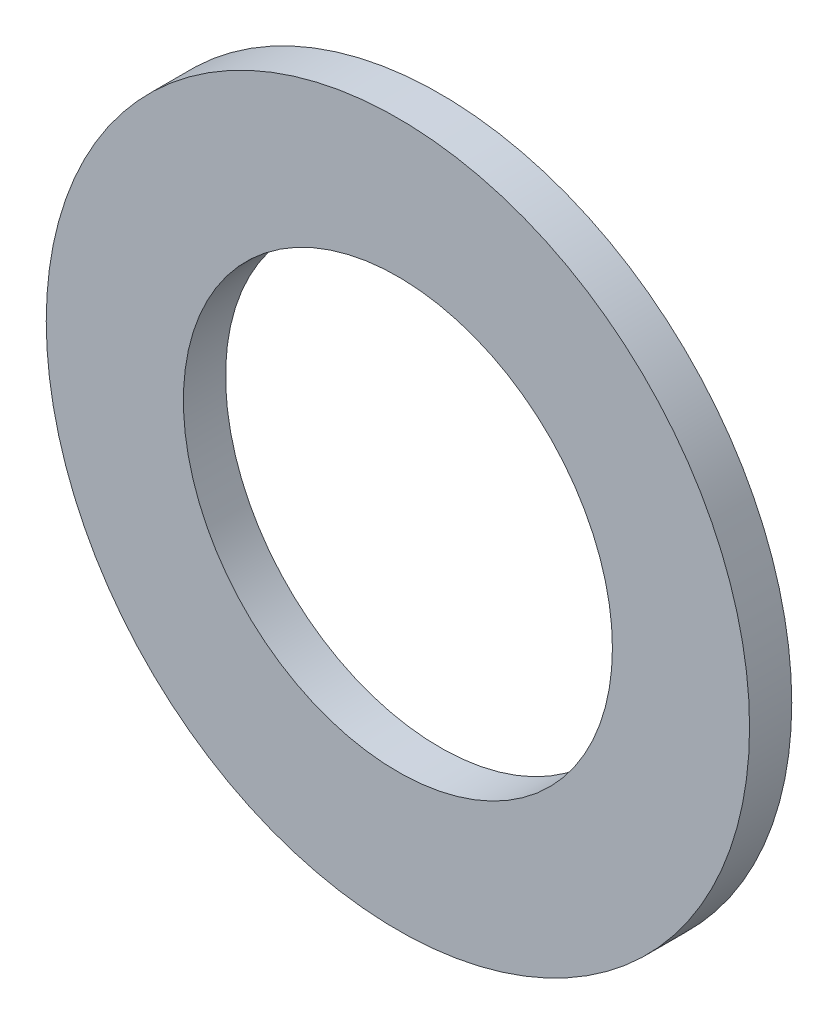
SolidWorks part; units mm, degrees
ref_plane "Front Plane" through (0, 0, 0) normal (0, 0, 1) x (1, 0, 0)
ref_plane "Top Plane" through (0, 0, 0) normal (0, 1, 0) x (1, 0, 0)
ref_plane "Right Plane" through (0, 0, 0) normal (1, 0, 0) x (0, 0, -1)
sketch "Sketch1" plane through (0, 0, 0) normal (1, 0, 0) x (0, 0, -1)
  line L0 (0, 0) -> (44.6003, 0) construction
  line L1 (0, 30.5) -> (0, 50)
  line L2 (0, 50) -> (6, 50)
  line L3 (6, 50) -> (6, 30.5)
  line L4 (6, 30.5) -> (0, 30.5)
  line L5 (0, 0) -> (0, 30.5) construction
  dimension "D1" = 100
  dimension "D2" = 61
  dimension "D3" = 6
revolve "Revolve1" add sketch "Sketch1" angle 360 about L0
